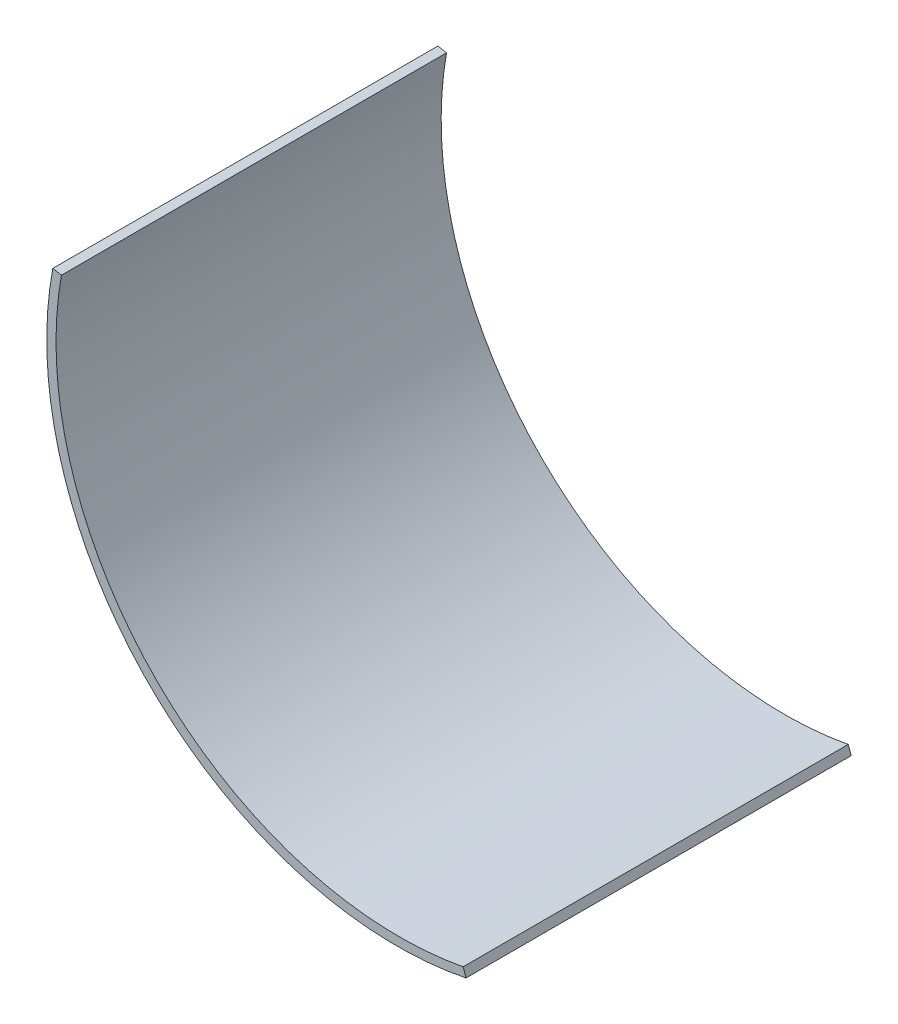
SolidWorks part; units mm, degrees
material "ABS PC"
ref_plane "Front Plane" through (0, 0, 0) normal (0, 0, 1) x (1, 0, 0)
ref_plane "Top Plane" through (0, 0, 0) normal (0, 1, 0) x (1, 0, 0)
ref_plane "Right Plane" through (0, 0, 0) normal (1, 0, 0) x (0, 0, -1)
sketch "Sketch1" plane through (0, 0, 0) normal (0, 0, 1) x (1, 0, 0)
  line L0 (-149.8919, 147.972) -> (-146.7716, 147.3852)
  line L1 (0, 0) -> (-1.0562, 2.9942)
  arc A0 (0, 0) -> (-149.8919, 147.972) centre (-25.0799, 124.499) cw
  arc A1 (-146.7716, 147.3852) -> (-1.0562, 2.9942) centre (-24.1423, 125.4177) ccw
  dimension "D3" = 127
  dimension "D1" = 3.175
  dimension "D2" = 3.175
extrude "Boss-Extrude1" add sketch "Sketch1" along normal blind 139.7
